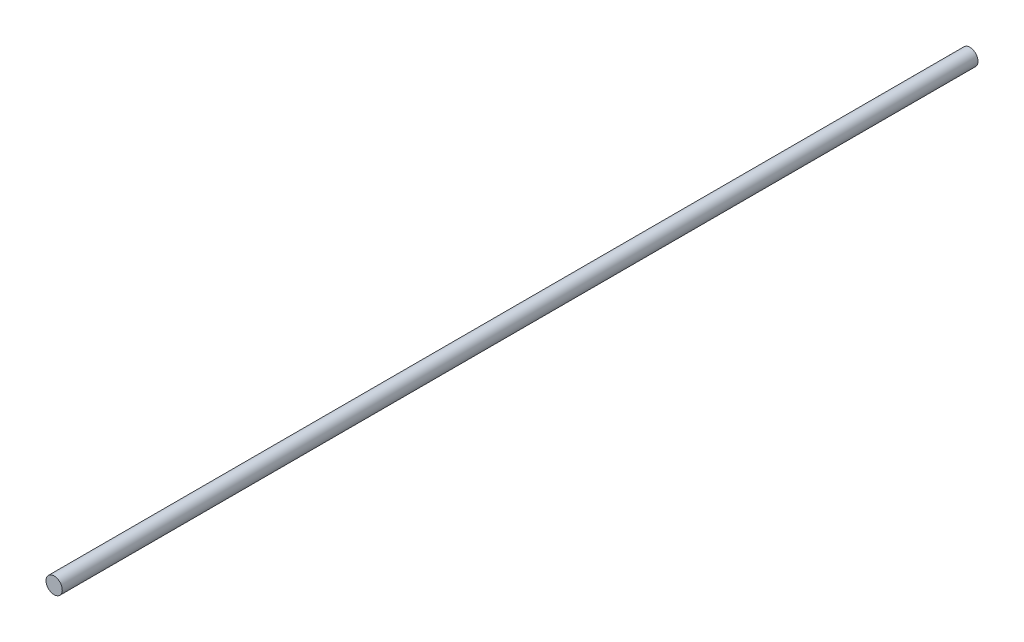
SolidWorks part; units mm, degrees
material "Acero inoxidable fundido"
ref_plane "Alzado" through (0, 0, 0) normal (0, 0, 1) x (1, 0, 0)
ref_plane "Planta" through (0, 0, 0) normal (0, 1, 0) x (1, 0, 0)
ref_plane "Vista lateral" through (0, 0, 0) normal (1, 0, 0) x (0, 0, -1)
sketch "Croquis1" plane through (0, 0, 0) normal (0, 0, 1) x (1, 0, 0)
  circle A0 centre (0, 0) radius 4
  dimension "D1" = 8
extrude "Saliente-Extruir1" add sketch "Croquis1" along normal blind 450
